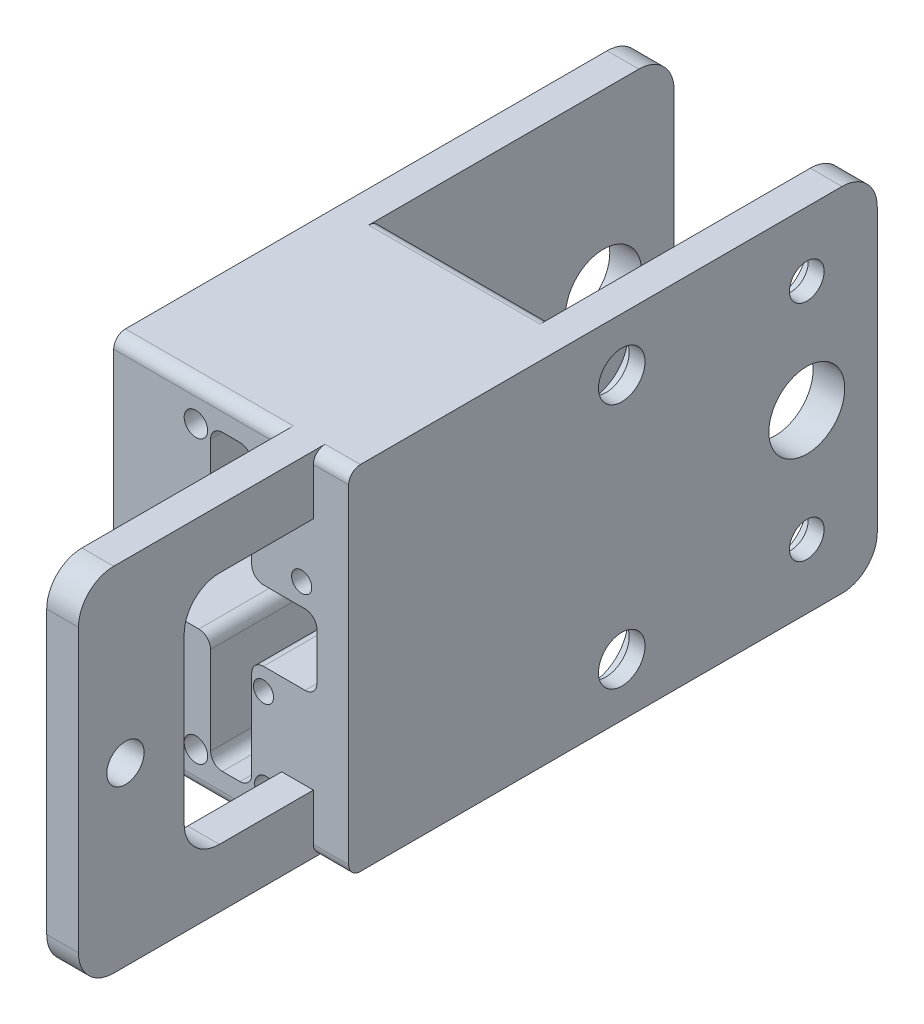
SolidWorks part; units mm, degrees
ref_plane "Front Plane" through (0, 0, 0) normal (0, 0, 1) x (1, 0, 0)
ref_plane "Top Plane" through (0, 0, 0) normal (0, 1, 0) x (1, 0, 0)
ref_plane "Right Plane" through (0, 0, 0) normal (1, 0, 0) x (0, 0, -1)
sketch "Sketch1" plane through (0, 0, 0) normal (0, 1, 0) x (1, 0, 0)
  line L0 (10, 5) -> (14, 5)
  line L1 (-10, -10) -> (10, -10)
  line L2 (-10, -10) -> (-10, 10)
  line L3 (-10, 10) -> (10, 10)
  line L4 (10, -10) -> (10, 10)
  line L5 (-10, -10) -> (10, 10) construction
  line L6 (-10, 10) -> (10, -10) construction
  line L7 (14, 5) -> (14, 3)
  line L8 (14, 3) -> (13, 3)
  line L9 (13, 3) -> (13, 4)
  line L10 (13, 4) -> (10, 4)
  line L11 (10, 4) -> (10, 5)
  line L19 (0, 10) -> (0, -10) construction
  point P0 (0, 0)
  dimension "D1" = 20
  dimension "D2" = 20
  dimension "D3" = 4
  dimension "D4" = 2
  dimension "D5" = 1
  dimension "D6" = 1
  dimension "D7" = 5
extrude "Boss-Extrude3" add sketch "Sketch1" along normal blind 30 contours L1 L4 L3 L2
sketch "Sketch10" plane through (0, 0, -10) normal (0, 0, -1) x (-1, 0, 0)
  line L0 (0, 30) -> (0, 0) construction
  line L1 (-1.75, 27.5) -> (1.75, 27.5)
  line L2 (10, 30) -> (-10, 30) construction
  line L11 (-10, 15) -> (10, 15) construction
  line L12 (-10, 30) -> (-10, 0) construction
  line L13 (10, 30) -> (10, 0) construction
  line L20 (1.75, 27.5) -> (1.75, 18)
  line L21 (1.75, 18) -> (7.3, 18)
  line L22 (7.3, 18) -> (7.3, 12)
  line L23 (-7.3, 18) -> (-7.3, 12)
  line L24 (-1.75, 18) -> (-7.3, 18)
  line L25 (-1.75, 27.5) -> (-1.75, 18)
  line L26 (-1.75, 2.5) -> (-1.75, 12)
  line L27 (-1.75, 12) -> (-7.3, 12)
  line L28 (1.75, 12) -> (7.3, 12)
  line L29 (1.75, 2.5) -> (1.75, 12)
  line L30 (-1.75, 2.5) -> (1.75, 2.5)
  circle A0 centre (-6, 19.86) radius 0.86
  circle A1 centre (-2.75, 10.14) radius 0.86
  point P10 (0, 15)
  point P21 (0, 27.5)
  point P24 (-7.3, 15)
  point P25 (7.3, 15)
  point P27 (0, 2.5)
  point P32 (2.75, 10.1794)
  dimension "D6" = 1.72
  dimension "D7" = 4
  dimension "D8" = 1.72
  dimension "D9" = 2.75
  dimension "D1" = 1.75
  dimension "D2" = 2.7
  dimension "D3" = 2.5
  dimension "D4" = 3
  dimension "D5" = 4.86
  dimension "D10" = 4.86
extrude "Cut-Extrude11" cut sketch "Sketch10" against normal up to next
fillet "Fillet4" radius 1 12 edges at (-1.75, 2.5, 0) (1.75, 2.5, 0) (-7.3, 12, 0) (-7.3, 18, 0) (-1.75, 12, 0) (1.75, 12, 0) (7.3, 12, 0) (7.3, 18, 0) (1.75, 18, 0) (-1.75, 18, 0) (-1.75, 27.5, 0) (1.75, 27.5, 0)
sketch "Sketch12" plane through (0, 0, 10) normal (0, 0, 1) x (1, 0, 0)
  line L0 (-10, 15) -> (10, 15) construction
  line L1 (-10, 30) -> (-10, 0) construction
  line L2 (10, 30) -> (10, 0) construction
  line L3 (-10, 30) -> (10, 30) construction
  line L16 (7, 0) -> (4.3, 0)
  line L25 (7, 0) -> (7, 30)
  line L26 (7, 30) -> (4.3, 30)
  line L27 (4.3, 0) -> (4.3, 30)
  line L28 (7, 0) -> (4.3, 30) construction
  line L29 (7, 30) -> (4.3, 0) construction
  point P4 (5.65, 15)
  dimension "D1" = 2.7
  dimension "D2" = 3
extrude "Boss-Extrude13" add sketch "Sketch12" along normal blind 20
sketch "Sketch14" plane through (7, 0, 0) normal (1, 0, 0) x (0, 0, -1)
  line L0 (-30, 15) -> (-10, 15) construction
  line L1 (-30, 0) -> (-30, 30) construction
  line L2 (-10, 30) -> (-10, 0) construction
  line L10 (-30, 30) -> (-10, 30) construction
  line L11 (-21, 5) -> (-10, 5)
  line L14 (-21, 5) -> (-21, 25)
  line L15 (-21, 25) -> (-10, 25)
  line L16 (-10, 5) -> (-10, 25)
  line L17 (-21, 5) -> (-10, 25) construction
  line L18 (-21, 25) -> (-10, 5) construction
  circle A0 centre (-26, 15) radius 1.59
  point P5 (-15.5, 15)
  dimension "D4" = 3.18
  dimension "D1" = 4
  dimension "D2" = 5
  dimension "D3" = 5
extrude "Cut-Extrude13" cut sketch "Sketch14" against normal up to next
fillet "Fillet6" radius 3 4 edges at (5.65, 30, 30) (5.65, 0, 30) (5.65, 25, 21) (5.65, 5, 21)
sketch "Sketch16" plane through (0, 0, -10) normal (0, 0, -1) x (-1, 0, 0)
  line L0 (-10, 15) -> (10, 15) construction
  line L1 (-10, 30) -> (-10, 0) construction
  line L2 (10, 30) -> (10, 0) construction
  line L3 (10, 30) -> (-10, 30) construction
  line L8 (7.3, 0) -> (10, 0)
  line L9 (7.3, 0) -> (7.3, 30)
  line L10 (7.3, 30) -> (10, 30)
  line L11 (10, 0) -> (10, 30)
  line L12 (7.3, 0) -> (10, 30) construction
  line L13 (7.3, 30) -> (10, 0) construction
  point P6 (8.65, 15)
  dimension "D1" = 2.7
extrude "Boss-Extrude14" add sketch "Sketch16" along normal blind 25
sketch "Sketch17" plane through (-7.3, 0, 0) normal (1, 0, 0) x (0, 0, -1)
  line L0 (35, 15) -> (10, 15) construction
  line L1 (35, 30) -> (35, 0) construction
  line L2 (10, 30) -> (10, 0) construction
  circle A0 centre (29, 15) radius 3.23
  dimension "D1" = 6.46
  dimension "D2" = 6
extrude "Cut-Extrude14" cut sketch "Sketch17" against normal up to next
fillet "Fillet11" radius 3 2 edges at (-8.65, 30, -35) (-8.65, 0, -35)
mirror "Mirror1" about plane through (0, 0, 0) normal (1, 0, 0) of "Cut-Extrude14", "Fillet11", "Boss-Extrude14"
fillet "Fillet12" radius 1 6 edges at (0, 30, -10) (0, 0, -10) (-2.85, 30, 10) (-2.85, 0, 10) (8.5, 0, 10) (8.5, 30, 10)
sketch "Sketch18" plane through (0, 0, -10) normal (0, 0, -1) x (-1, 0, 0)
  line L0 (0, 29) -> (0, 0) construction
  line L1 (7.3, 29) -> (-7.3, 29) construction
  line L5 (-7.3, 1) -> (7.3, 1) construction
  circle A0 centre (-3, 27) radius 1
  circle A1 centre (3, 3) radius 1
  dimension "D1" = 2
  dimension "D2" = 2
  dimension "D3" = 3
  dimension "D4" = 2
  dimension "D5" = 2
  dimension "D6" = 3
extrude "Cut-Extrude15" cut sketch "Sketch18" against normal up to next
mirror "Mirror2" about plane through (0, 0, 0) normal (1, 0, 0) of "Cut-Extrude15"
sketch "Sketch20" plane through (-7.3, 0, 0) normal (-1, 0, 0) x (0, 0, 1)
  line L1 (-10, 29) -> (-10, 17) construction
  line L2 (-10, 15) -> (-35, 15) construction
  line L3 (-35, 27) -> (-35, 3) construction
  line L4 (-10, 17) -> (-10, 13) construction
  line L5 (9, 0) -> (-32, 0) construction
  line L6 (9, 30) -> (-32, 30) construction
  circle A0 centre (-13.25, 25.48) radius 1.98
  circle A1 centre (-13.25, 4.52) radius 1.98
  circle A2 centre (-29, 5.48) radius 1.475
  circle A3 centre (-29, 24.52) radius 1.475
  dimension "D1" = 3.96
  dimension "D2" = 4.52
  dimension "D3" = 3.25
  dimension "D4" = 2.95
  dimension "D5" = 5.48
  dimension "D6" = 6
extrude "Cut-Extrude16" cut sketch "Sketch20" against normal up to next
sketch "Sketch22" plane through (7.3, 0, 0) normal (-1, 0, 0) x (0, 0, 1)
  line L0 (-35, 15) -> (-10, 15) construction
  line L1 (-35, 27) -> (-35, 3) construction
  line L2 (-10, 17) -> (-10, 13) construction
  circle A0 centre (-29, 24.52) radius 2.725
  circle A1 centre (-29, 24.52) radius 1.475 construction
  circle A2 centre (-13.25, 25.48) radius 3.23
  circle A3 centre (-13.25, 25.48) radius 1.98 construction
  circle A4 centre (-13.25, 4.52) radius 3.23
  circle A5 centre (-29, 5.48) radius 2.725
  point P18 (-10, 15)
  dimension "D1" = 1.25
  dimension "D2" = 1.25
extrude "Cut-Extrude17" cut sketch "Sketch22" against normal blind 1.35
